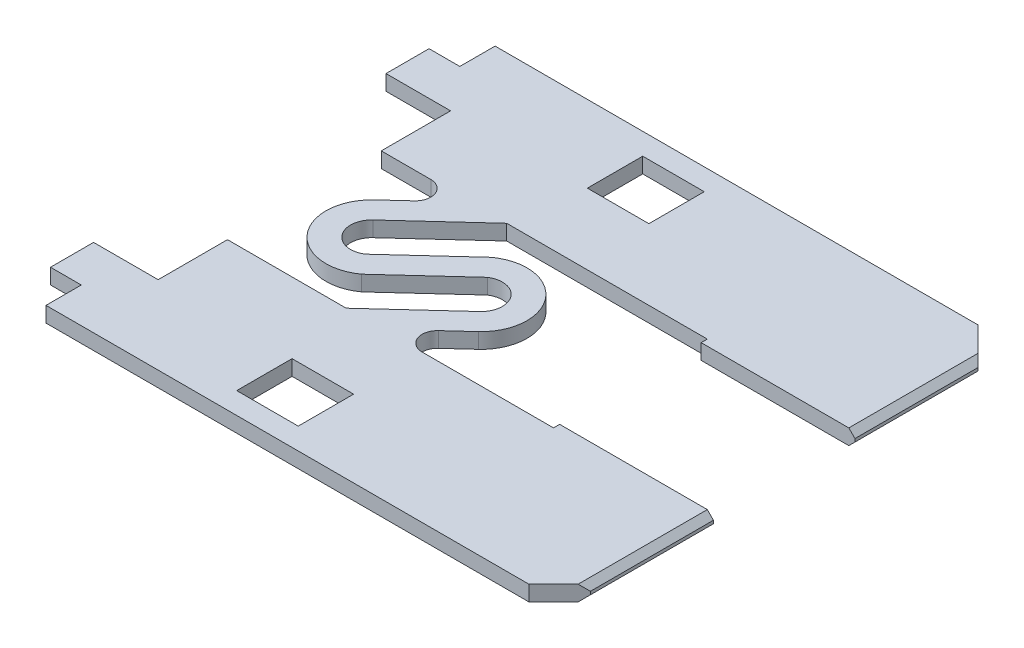
SolidWorks part; units mm, degrees
ref_plane "Front Plane" through (0, 0, 0) normal (0, 0, 1) x (1, 0, 0)
ref_plane "Top Plane" through (0, 0, 0) normal (0, 1, 0) x (1, 0, 0)
ref_plane "Right Plane" through (0, 0, 0) normal (1, 0, 0) x (0, 0, -1)
sketch "Sketch1" plane through (0, 0, 0) normal (0, 1, 0) x (1, 0, 0)
  line L0 (-6.7446, 7.3) -> (8.9554, 7.3)
  line L1 (8.9554, 7.3) -> (9.9554, 6.3)
  line L2 (9.9554, 6.3) -> (9.9554, 2.3)
  line L3 (9.9554, 2.3) -> (4.9554, 2.3)
  line L4 (4.9554, 2.3) -> (4.9554, 2.5)
  line L5 (0.679, -2.5) -> (4.9554, -2.5)
  line L6 (-5.6446, 2.5) -> (-5.6446, 4.7536)
  line L7 (-5.6446, 4.7536) -> (-7.7446, 4.7536)
  line L8 (-7.7446, 4.7536) -> (-7.7446, 6.1536)
  line L9 (-7.7446, 6.1536) -> (-6.7446, 6.1536)
  line L10 (-6.7446, 6.1536) -> (-6.7446, 7.3)
  line L11 (-13.2813, 0) -> (9.1797, 0) construction
  line L12 (-6.7446, -6.1536) -> (-6.7446, -7.3)
  line L13 (-7.7446, -6.1536) -> (-6.7446, -6.1536)
  line L14 (-7.7446, -4.7536) -> (-7.7446, -6.1536)
  line L15 (-5.6446, -4.7536) -> (-7.7446, -4.7536)
  line L16 (-5.6446, -2.5) -> (-5.6446, -4.7536)
  line L17 (4.9554, 2.5) -> (-1.5657, 2.5)
  line L18 (4.9554, -2.3) -> (4.9554, -2.5)
  line L19 (9.9554, -2.3) -> (4.9554, -2.3)
  line L20 (9.9554, -6.3) -> (9.9554, -2.3)
  line L21 (8.9554, -7.3) -> (9.9554, -6.3)
  line L22 (-6.7446, -7.3) -> (8.9554, -7.3)
  line L23 (-1.5657, 2.5) -> (-3.8331, 0.4212)
  line L24 (-1.2446, 6.6) -> (0.7554, 6.6)
  line L25 (-1.2446, 6.6) -> (-1.2446, 4.8)
  line L26 (-1.2446, 4.8) -> (0.7554, 4.8)
  line L27 (0.7554, 6.6) -> (0.7554, 4.8)
  line L28 (-2.9923, -0.6646) -> (-2.2674, 0)
  line L29 (-3.6968, 1.6315) -> (-4.3737, 1.0108)
  line L30 (-2.4914, -1.2907) -> (-1.0836, 0)
  line L31 (-5.6446, -2.5) -> (-1.7852, -2.5)
  line L32 (-4.0347, 2.5) -> (-5.6446, 2.5)
  line L36 (-1.2446, -4.8) -> (0.7554, -4.8)
  line L37 (0.7554, -6.6) -> (0.7554, -4.8)
  line L38 (-1.2446, -6.6) -> (-1.2446, -4.8)
  line L39 (-1.2446, -6.6) -> (0.7554, -6.6)
  line L40 (-1.7852, -2.5) -> (0.4821, -0.4212)
  line L41 (0.3459, -1.6315) -> (1.0228, -1.0108)
  line L42 (-0.3587, 0.6646) -> (-1.0836, 0)
  line L43 (-0.8596, 1.2907) -> (-2.2674, 0)
  arc A0 (-3.8331, 0.4212) -> (-2.9923, -0.6646) centre (-3.3675, -0.0867) ccw
  arc A1 (-4.3737, 1.0108) -> (-2.4914, -1.2907) centre (-3.3675, -0.0867) ccw
  arc A2 (-3.6968, 1.6315) -> (-4.0347, 2.5) centre (-4.0347, 2) ccw
  arc A6 (0.3459, -1.6315) -> (0.679, -2.5) centre (0.6837, -2) ccw
  arc A7 (1.0228, -1.0108) -> (-0.8596, 1.2907) centre (0.0165, 0.0867) ccw
  arc A8 (0.4821, -0.4212) -> (-0.3587, 0.6646) centre (0.0165, 0.0867) ccw
  point P34 (0.161, 3.0897)
  point P36 (-2.1064, 1.0108)
  point P42 (-0.4821, 2.5)
  dimension "D13" = 0.5
  dimension "D1" = 5
  dimension "D2" = 1.8
  dimension "D3" = 4
  dimension "D4" = 45
  dimension "D5" = 2
  dimension "D6" = 0.7
  dimension "D7" = 1.4
  dimension "D8" = 4.4
  dimension "D9" = 2.3
  dimension "D10" = 5
  dimension "D11" = 1
  dimension "D14" = 6.5
  dimension "D12" = 17.7
extrude "Boss-Extrude1" add sketch "Sketch1" along normal blind 0.5
chamfer "Chamfer1" distance 0.2 4 edges at (9.9554, 0, -4.3) (9.9554, 0, 4.3) (9.9554, 0.5, -4.3) (9.9554, 0.5, 4.3)
